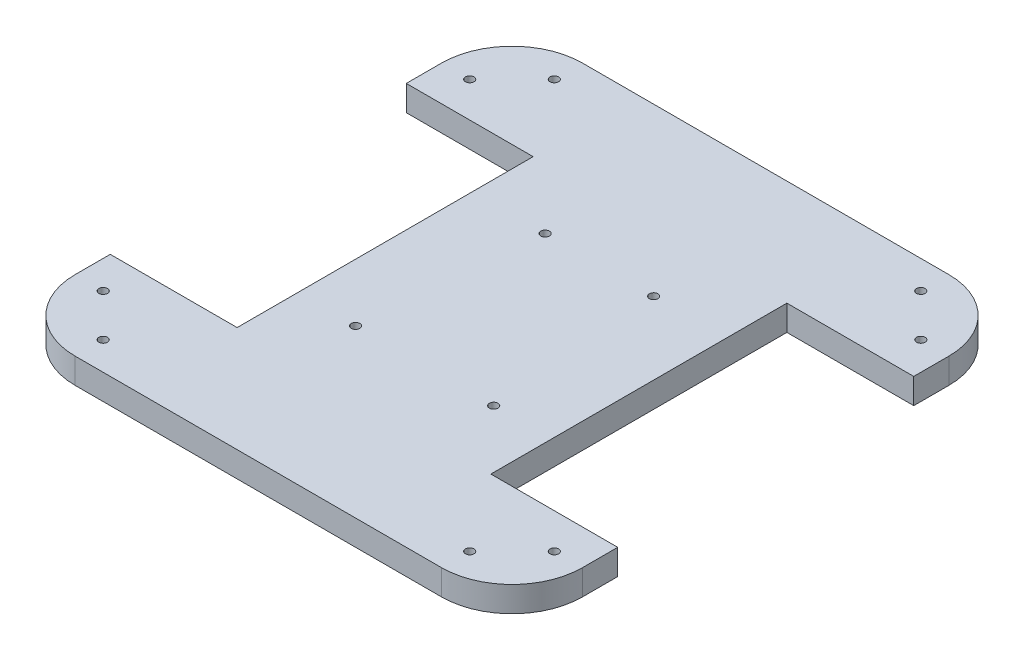
SolidWorks part; units mm, degrees
ref_plane "Front Plane" through (0, 0, 0) normal (0, 0, 1) x (1, 0, 0)
ref_plane "Top Plane" through (0, 0, 0) normal (0, 1, 0) x (1, 0, 0)
ref_plane "Right Plane" through (0, 0, 0) normal (1, 0, 0) x (0, 0, -1)
sketch "Sketch1" plane through (0, 0, 0) normal (0, 1, 0) x (1, 0, 0)
  line L1 (-65, -90) -> (65, -90)
  line L2 (-90, -65) -> (-90, 65)
  line L3 (-65, 90) -> (65, 90)
  line L4 (90, -65) -> (90, 65)
  arc A0 (-90, 65) -> (-65, 90) centre (-65, 65) cw
  arc A1 (65, 90) -> (90, 65) centre (65, 65) cw
  arc A2 (90, -65) -> (65, -90) centre (65, -65) cw
  arc A3 (-65, -90) -> (-90, -65) centre (-65, -65) cw
  point P4 (-90, 0)
  point P6 (0, 90)
  dimension "D3" = 25
  dimension "D1" = 180
  dimension "D2" = 180
extrude "Plate" add sketch "Sketch1" along normal blind 9
sketch "Sketch3" plane through (0, 9, 0) normal (0, 1, 0) x (1, 0, 0)
  line L0 (-65, 90) -> (-65, -90) construction
  line L1 (65, 90) -> (65, -90) construction
  line L2 (-90, 65) -> (90, 65) construction
  line L3 (-90, -65) -> (90, -65) construction
  circle A0 centre (-65, 80) radius 1.525
  circle A1 centre (-80, 65) radius 1.525
  circle A2 centre (80, 65) radius 1.525
  circle A3 centre (80, -65) radius 1.525
  circle A4 centre (65, 80) radius 1.525
  circle A5 centre (65, -80) radius 1.525
  circle A6 centre (-65, -80) radius 1.525
  circle A7 centre (-80, -65) radius 1.525
  dimension "D1" = 3.05
  dimension "D2" = 15
  dimension "D3" = 15
  dimension "D4" = 15
  dimension "D5" = 15
  dimension "D6" = 15
  dimension "D7" = 15
  dimension "D8" = 15
  dimension "D9" = 15
extrude "Hex Holes" cut sketch "Sketch3" against normal through all
sketch "Sketch4" plane through (0, 9, 0) normal (0, 1, 0) x (1, 0, 0)
  line L0 (-90, -65) -> (-90, 65) construction
  line L1 (-65, -90) -> (65, -90) construction
  circle A0 centre (-24.5, -31) radius 1.525
  circle A1 centre (24.5, -31) radius 1.525
  circle A2 centre (-19.25, 31) radius 1.525
  circle A3 centre (19.25, 31) radius 1.525
  dimension "D1" = 3.05
  dimension "D2" = 62
  dimension "D3" = 49
  dimension "D4" = 5.25
  dimension "D5" = 38.5
  dimension "D6" = 65.5
  dimension "D7" = 59
extrude "Arduino Holes" cut sketch "Sketch4" against normal through all
sketch "Sketch5" plane through (0, 9, 0) normal (0, 1, 0) x (1, 0, 0)
  line L0 (-90, 52.5) -> (-45, 52.5)
  line L1 (-90, -65) -> (-90, 65) construction
  line L2 (-45, 52.5) -> (-45, -52.5)
  line L3 (-45, -52.5) -> (-90, -52.5)
  line L4 (-90, 52.5) -> (-90, -52.5)
  line L5 (90, -65) -> (90, 65) construction
  line L6 (90, 52.5) -> (45, 52.5)
  line L7 (90, 52.5) -> (90, -52.5)
  line L8 (90, -52.5) -> (45, -52.5)
  line L9 (45, 52.5) -> (45, -52.5)
  line L10 (-90, 0) -> (90, 0) construction
  point P15 (0, 0)
  point P16 (-90, 0)
  point P17 (90, 0)
  dimension "D1" = 105
  dimension "D2" = 45
extrude "Cut-Extrude1" cut sketch "Sketch5" against normal through all
